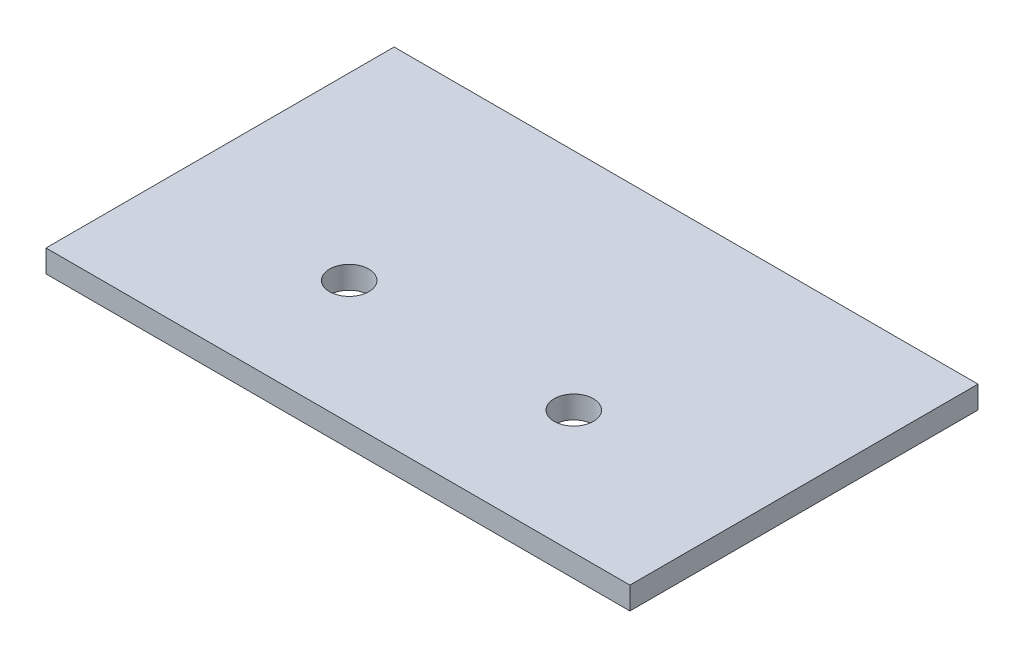
SolidWorks part; units mm, degrees
ref_plane "Alzado" through (0, 0, 0) normal (0, 0, 1) x (1, 0, 0)
ref_plane "Planta" through (0, 0, 0) normal (0, 1, 0) x (1, 0, 0)
ref_plane "Vista lateral" through (0, 0, 0) normal (1, 0, 0) x (0, 0, -1)
sketch "Sketch1" plane through (0, 0, 0) normal (0, 1, 0) x (1, 0, 0)
  line L1 (-26, 15.5) -> (26, 15.5)
  line L2 (-26, 15.5) -> (-26, -15.5)
  line L3 (-26, -15.5) -> (26, -15.5)
  line L4 (26, 15.5) -> (26, -15.5)
  line L5 (-26, 15.5) -> (26, -15.5) construction
  line L6 (-26, -15.5) -> (26, 15.5) construction
  circle A0 centre (-10, -4.5) radius 1.75
  circle A1 centre (10, -4.5) radius 1.75
  point P0 (0, 0)
  dimension "D6" = 3.5
  dimension "D7" = 3.5
  dimension "D1" = 52
  dimension "D2" = 31
  dimension "D3" = 20
  dimension "D4" = 20
  dimension "D5" = 10
extrude "Boss-Extrude1" add sketch "Sketch1" along normal blind 2
